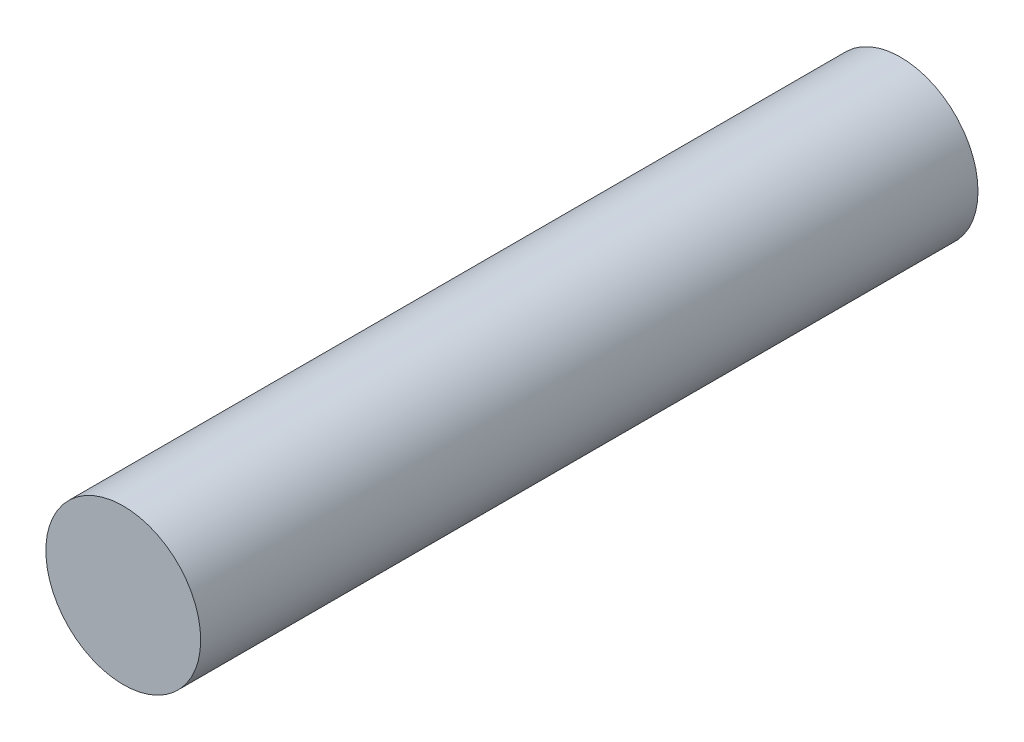
SolidWorks part; units mm, degrees
ref_plane "Front Plane" through (0, 0, 0) normal (0, 0, 1) x (1, 0, 0)
ref_plane "Top Plane" through (0, 0, 0) normal (0, 1, 0) x (1, 0, 0)
ref_plane "Right Plane" through (0, 0, 0) normal (1, 0, 0) x (0, 0, -1)
sketch "Sketch1" plane through (0, 0, 0) normal (0, 0, 1) x (1, 0, 0)
  circle A0 centre (0, 0) radius 2.49
  dimension "D1" = 4.98
extrude "Boss-Extrude1" add sketch "Sketch1" along normal blind 15 and the other way blind 10
sketch "Sketch2" plane through (0, 0, 0) normal (0, 0, 1) x (1, 0, 0)
  circle A0 centre (0, 0) radius 2.5 construction
  dimension "D1" = 5
